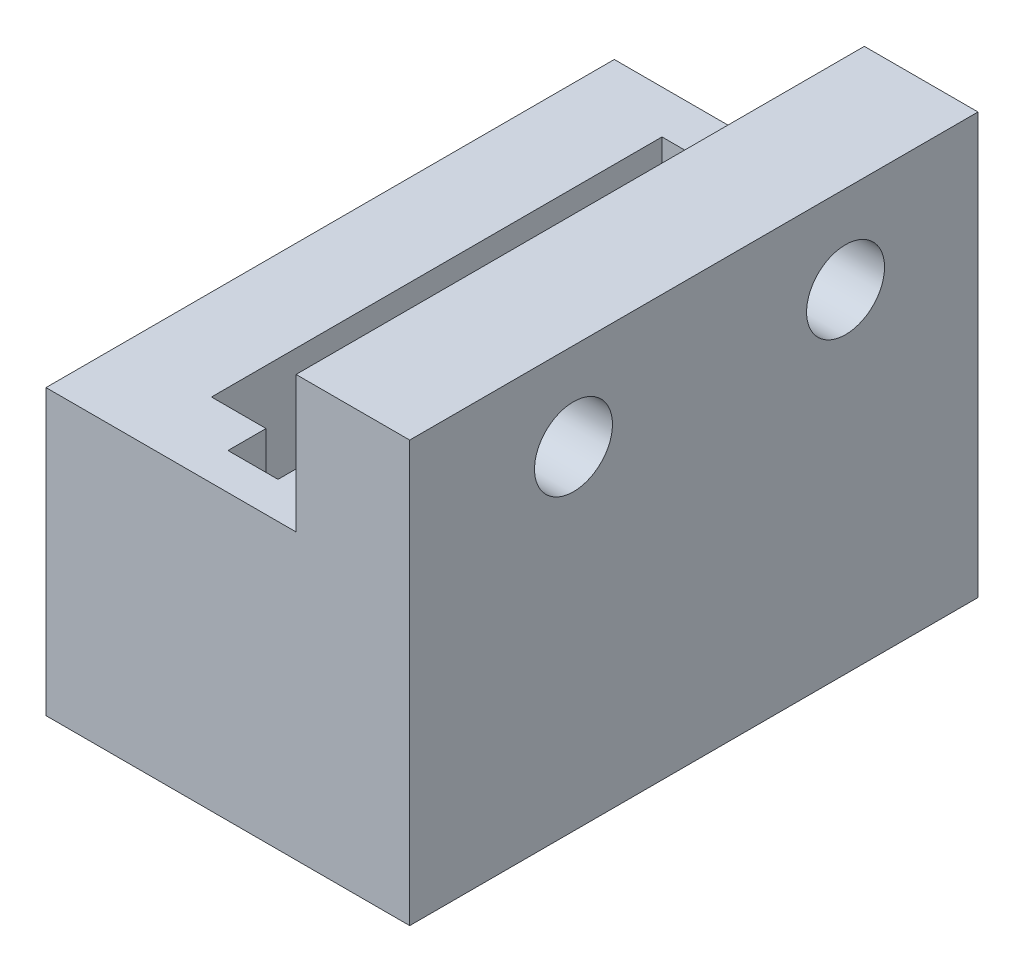
SolidWorks part; units mm, degrees
ref_plane "Front Plane" through (0, 0, 0) normal (0, 0, 1) x (1, 0, 0)
ref_plane "Top Plane" through (0, 0, 0) normal (0, 1, 0) x (1, 0, 0)
ref_plane "Right Plane" through (0, 0, 0) normal (1, 0, 0) x (0, 0, -1)
sketch "Sketch1" plane through (0, 0, 0) normal (0, 1, 0) x (1, 0, 0)
  line L1 (0, 0) -> (16, 0)
  line L2 (0, 0) -> (0, 25)
  line L3 (0, 25) -> (16, 25)
  line L4 (16, 0) -> (16, 25)
  dimension "D1" = 25
  dimension "D2" = 16
extrude "Boss-Extrude1" add sketch "Sketch1" along normal blind 12.5
sketch "Sketch2" plane through (0, 12.5, 0) normal (0, 1, 0) x (1, 0, 0)
  line L0 (16, 0) -> (16, 25) construction
  line L1 (4, 23.0983) -> (6.4, 23.0983)
  line L2 (4, 23.0983) -> (4, 3.2803)
  line L3 (4, 3.2803) -> (6.4, 3.2803)
  line L4 (11, 23.0983) -> (11, 3.2803)
  line L5 (7.5, 25) -> (7.5, 1.6053) construction
  line L6 (6.4, 23.0983) -> (6.4, 25)
  line L7 (16, 25) -> (0, 25) construction
  line L8 (6.4, 25) -> (8.6, 25)
  line L9 (8.6, 25) -> (8.6, 23.0983)
  line L10 (8.6, 23.0983) -> (11, 23.0983)
  line L11 (6.4, 3.2803) -> (6.4, 1.6053)
  line L12 (6.4, 1.6053) -> (8.6, 1.6053)
  line L13 (8.6, 1.6053) -> (8.6, 3.2803)
  line L14 (8.6, 3.2803) -> (11, 3.2803)
  dimension "D1" = 19.818
  dimension "D2" = 7
  dimension "D3" = 5
  dimension "D4" = 2.2
  dimension "D5" = 1.675
extrude "Cut-Extrude1" cut sketch "Sketch2" against normal blind 6.056
ref_plane "PLANE-CAVITY-MIDLINE" through (7.5, 0, 0) normal (1, 0, 0) x (0, 0, -1)
sketch "Sketch4" plane through (0, 12.5, 0) normal (0, 1, 0) x (1, 0, 0)
  line L0 (0, 0) -> (16, 0) construction
  line L1 (11, 0) -> (16, 0)
  line L2 (11, 0) -> (11, 25)
  line L3 (11, 25) -> (16, 25)
  line L4 (16, 0) -> (16, 25)
  line L5 (11, 3.2803) -> (11, 23.0983) construction
extrude "Boss-Extrude2" add sketch "Sketch4" along normal blind 6
sketch "Sketch3" plane through (16, 0, 0) normal (1, 0, 0) x (0, 0, -1)
  line L0 (3.2803, 6.444) -> (23.0983, 6.444) construction
  line L3 (3.2803, 6.444) -> (23.0983, 6.444) construction
  line L8 (13.1893, 6.444) -> (13.1893, -49993.556) construction
  circle A0 centre (7.2053, 14.644) radius 1.7145
  circle A1 centre (19.1733, 14.644) radius 1.7145
  circle A2 centre (7.2053, 14.644) radius 1.25 construction
  point P7 (13.1893, 6.444)
  dimension "D1" = 3.429
  dimension "D2" = 10.2535
extrude "Cut-Extrude2" cut sketch "Sketch3" against normal up to surface (5 mm away) up to face at (11, 12.486, -12.8446)
sketch "Sketch6" plane through (0, 6.444, 0) normal (0, 1, 0) x (1, 0, 0)
  line L0 (5.875, 9.6053) -> (5.875, 3.2803) construction
  line L1 (4, 3.2803) -> (6.4, 3.2803) construction
  line L2 (9.125, 3.2803) -> (9.125, 9.6053) construction
  line L3 (8.6, 3.2803) -> (11, 3.2803) construction
  line L4 (9.125, 9.6053) -> (9.125, 17.6053) construction
  line L5 (9.125, 17.6053) -> (5.875, 17.6053) construction
  line L6 (5.875, 17.6053) -> (5.875, 9.6053) construction
  line L7 (5.875, 9.6053) -> (7.5, 9.6053) construction
  line L8 (7.5, -6.6308) -> (7.5, 6.6308) construction
  line L9 (7.5, 9.6053) -> (9.125, 9.6053) construction
  circle A0 centre (5.875, 9.6053) radius 0.5
  circle A1 centre (9.125, 9.6053) radius 0.5
  circle A2 centre (5.875, 17.6053) radius 0.5
  circle A3 centre (9.125, 17.6053) radius 0.5
  dimension "D1" = 1
  dimension "D2" = 8
  dimension "D3" = 1.625
  dimension "D4" = 6.325
extrude "Cut-Extrude3" cut sketch "Sketch6" against normal blind 4
sketch "Sketch7" plane through (0, 6.444, 0) normal (0, 1, 0) x (1, 0, 0)
  line L0 (7.5, 1.6053) -> (7.5, 5.6053) construction
  line L1 (6.4, 1.6053) -> (8.6, 1.6053) construction
  line L2 (7.5, -6.6308) -> (7.5, 6.6308) construction
  line L3 (7.5, 5.6053) -> (7.5, 13.6053) construction
  line L4 (7.5, 13.6053) -> (7.5, 21.6053) construction
  line L5 (8.6, 3.2803) -> (11, 3.2803) construction
  circle A0 centre (7.5, 21.6053) radius 1.5
  circle A1 centre (7.5, 13.6053) radius 1.5
  circle A2 centre (7.5, 5.6053) radius 1.5
  dimension "D2" = 8
  dimension "D3" = 8
  dimension "D1" = 2.325
  dimension "D4" = 3
extrude "Cut-Extrude4" cut sketch "Sketch7" against normal blind 2
